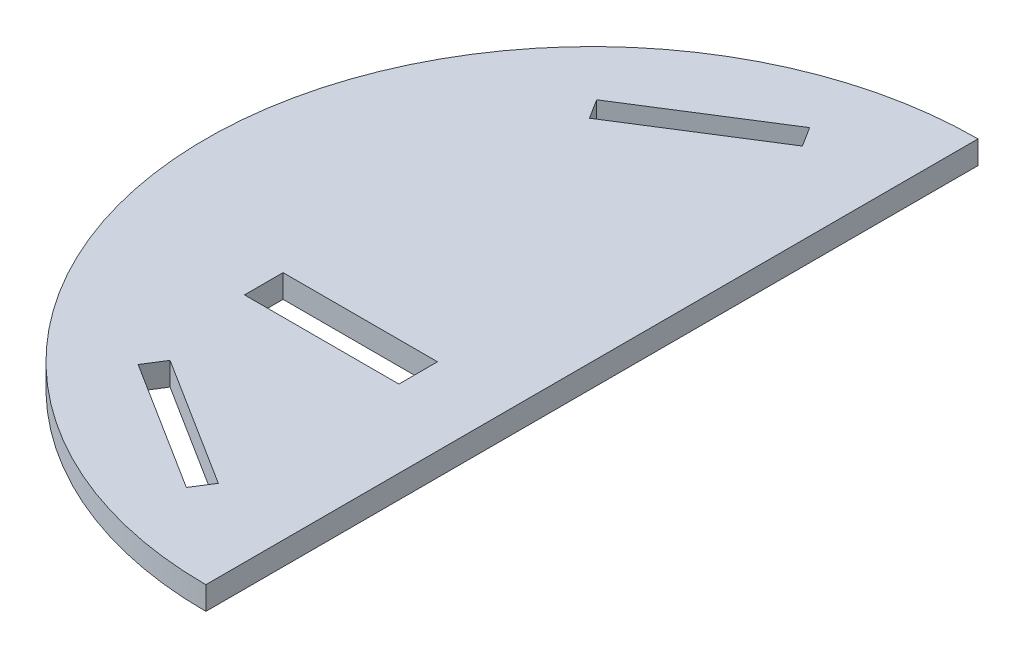
SolidWorks part; units mm, degrees
ref_plane "前视基准面" through (0, 0, 0) normal (0, 0, 1) x (1, 0, 0)
ref_plane "上视基准面" through (0, 0, 0) normal (0, 1, 0) x (1, 0, 0)
ref_plane "右视基准面" through (0, 0, 0) normal (1, 0, 0) x (0, 0, -1)
sketch "草图1" plane through (0, 0, 0) normal (0, 1, 0) x (1, 0, 0)
  line L0 (0, 50) -> (0, -50)
  arc A0 (0, 50) -> (0, -50) centre (0, 0) ccw
  point P0 (0, -50)
  point P1 (0, 50)
  point P2 (-50, 0)
extrude "凸台-拉伸1" add sketch "草图1" along normal blind 3 contours L0 A0
sketch "草图3" plane through (0, 3, 0) normal (0, 1, 0) x (1, 0, 0)
  line L0 (-29.0799, 29.6928) -> (-12.1633, 40.3618)
  line L1 (-29.0799, 29.6928) -> (-27.4796, 27.1553)
  line L2 (-27.4796, 27.1553) -> (-10.5629, 37.8243)
  line L3 (-10.5629, 37.8243) -> (-12.1633, 40.3618)
  line L4 (0, 0) -> (-50, 0)
  line L5 (0, 50) -> (0, -50) construction
  line L6 (-29.0799, -29.6928) -> (-27.4796, -27.1553)
  line L7 (-27.4796, -27.1553) -> (-10.5629, -37.8243)
  line L8 (-10.5629, -37.8243) -> (-12.1633, -40.3618)
  line L9 (-29.0799, -29.6928) -> (-12.1633, -40.3618)
  arc A0 (0, 50) -> (0, -50) centre (0, 0) ccw construction
  point P11 (-10.5629, -37.8243)
  point P12 (-12.1633, -40.3618)
  point P13 (-27.4796, -27.1553)
  point P14 (-29.0799, -29.6928)
  dimension "D1" = 20
  dimension "D2" = 3
extrude "切除-拉伸1" cut sketch "草图3" against normal blind 5 contours L2 L3 L0 L1 | L6 L9 L8 L7
sketch "草图4" plane through (0, 3, 0) normal (0, 1, 0) x (1, 0, 0)
  line L0 (-30, -10) -> (-30, -15)
  line L1 (-30, -15) -> (-10, -15)
  line L2 (-10, -15) -> (-10, -10)
  line L3 (-10, -10) -> (-29.4426, -10)
  line L4 (-30, -10) -> (-30, -15)
  line L5 (-30, -10) -> (-10, -10)
  line L6 (-30, -15) -> (-10, -15)
  line L7 (-10, -10) -> (-10, -15)
  point P0 (-30, -15)
  point P1 (-30, -10)
  point P2 (-10, -15)
  point P3 (-10, -10)
  dimension "D1" = 20
  dimension "D2" = 5
extrude "切除-拉伸2" cut sketch "草图4" against normal blind 5 contours L5 L0 L1 L2 L3
